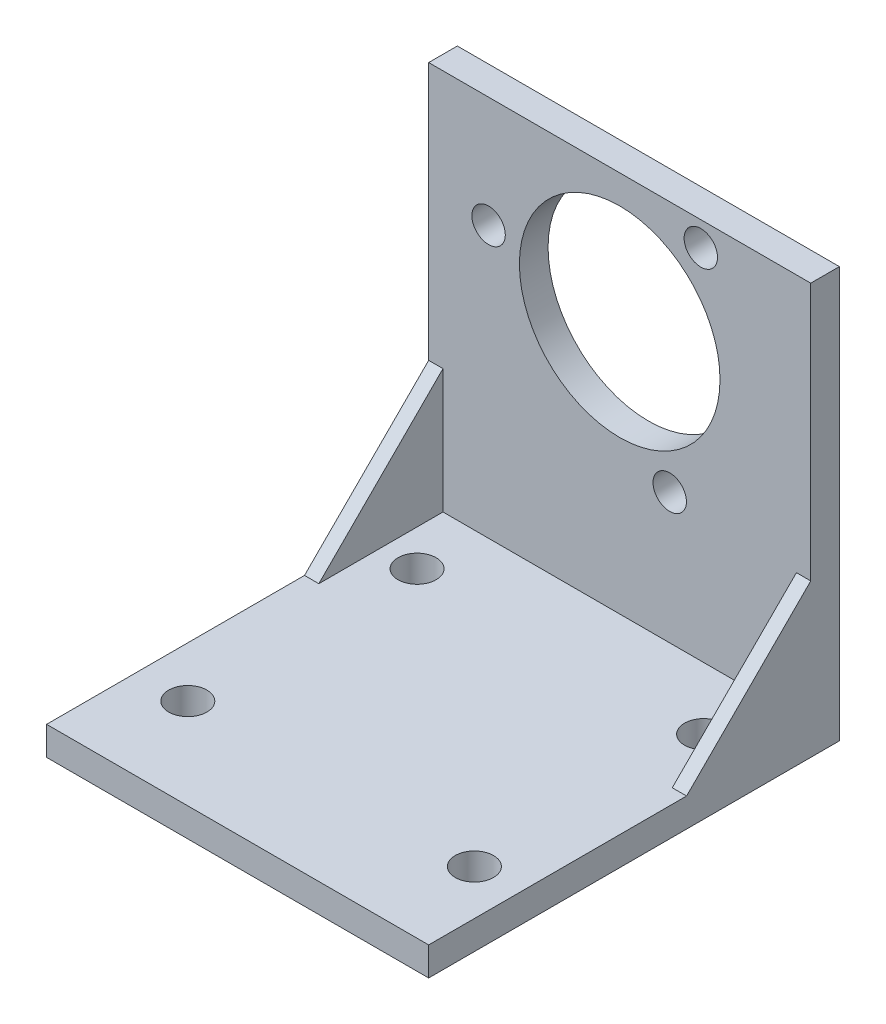
SolidWorks part; units mm, degrees
ref_plane "Front Plane" through (0, 0, 0) normal (0, 0, 1) x (1, 0, 0)
ref_plane "Top Plane" through (0, 0, 0) normal (0, 1, 0) x (1, 0, 0)
ref_plane "Right Plane" through (0, 0, 0) normal (1, 0, 0) x (0, 0, -1)
sketch "Sketch1" plane through (0, 0, 0) normal (0, 1, 0) x (1, 0, 0)
  line L0 (-20, 19.5) -> (20, 19.5)
  line L1 (-20, -21.5) -> (20, -21.5)
  line L2 (-20, -21.5) -> (-20, 21.5)
  line L3 (-20, 21.5) -> (20, 21.5)
  line L4 (20, -21.5) -> (20, 21.5)
  line L5 (-20, -21.5) -> (20, 21.5) construction
  line L6 (-20, 21.5) -> (20, -21.5) construction
  circle A7 centre (-14.7151, 12) radius 2
  circle A8 centre (15.2849, 12) radius 2
  circle A9 centre (-14.7151, -12) radius 2
  circle A10 centre (15.2849, -12) radius 2
  point P0 (0, 0)
  dimension "D4" = 30
  dimension "D5" = 4
  dimension "D6" = 4
  dimension "D7" = 24
  dimension "D8" = 9.5
  dimension "D9" = 5.2849
  dimension "D10" = 4
  dimension "D12" = 4
  dimension "D1" = 2
  dimension "D2" = 40
  dimension "D3" = 43
  dimension "D11" = 9.5
extrude "Boss-Extrude1" add sketch "Sketch1" against normal blind 3
sketch "Sketch4" plane through (0, 0, 0) normal (0, 1, 0) x (1, 0, 0)
  line L1 (-20, -21.5) -> (-20, 21.5) construction
  line L2 (20, -21.5) -> (20, 21.5) construction
  line L5 (-20, 21.5) -> (20, 21.5)
  line L6 (-20, 21.5) -> (-20, 18.5)
  line L7 (-20, 18.5) -> (20, 18.5)
  line L8 (-20, -21.5) -> (20, -21.5)
  line L9 (20, -21.5) -> (20, 21.5)
  line L10 (20, 21.5) -> (-20, 21.5)
  line L11 (-20, 21.5) -> (-20, -21.5)
  line L12 (-20, -21.5) -> (20, -21.5)
  line L13 (20, -21.5) -> (20, 12.2)
  line L15 (-20, 12.2) -> (-20, -21.5)
  line L16 (20, 21.5) -> (20, 18.5)
  line M13 (20, -21.5) -> (20, 21.5)
  line M14 (20, 21.5) -> (-20, 21.5)
  line M15 (-20, 21.5) -> (-20, -21.5)
  dimension "D1" = 3
  dimension "D2" = 0
extrude "Boss-Extrude2" add sketch "Sketch4" along normal blind 40 contours L7 M15 M13 M14
sketch "Sketch5" plane through (0, 0, -18.5) normal (0, 0, 1) x (1, 0, 0)
  line L0 (-20, 40) -> (20, -3) construction
  line L1 (-20, -3) -> (20, 40) construction
  line L2 (0, 26.5) -> (0, 40) construction
  line L5 (-20, 40) -> (20, 40) construction
  circle A0 centre (0, 26.5) radius 13.8564
  circle A2 centre (8.492, 37.4493) radius 1.75
  circle A3 centre (-13.7283, 28.3796) radius 1.75
  circle A4 centre (5.2364, 13.6711) radius 1.75
  circle A5 centre (0, 26.5) radius 10.5
  point P13 (0, 26.5)
  point P18 (0, 19.5)
  dimension "D2" = 24
  dimension "D3" = 24
  dimension "D4" = 13.5
  dimension "D5" = 3.5
  dimension "D1" = 24
  dimension "D6" = 3.5
  dimension "D7" = 3.5
extrude "Cut-Extrude1" cut sketch "Sketch5" against normal blind 24 contours A5 | A0 A3 | A0 A3 | A0 A4 | A0 A2 | A0 A2
sketch "Sketch7" plane through (20, 0, 0) normal (1, 0, 0) x (0, 0, -1)
  line L0 (18.5, 0) -> (18.5, 13)
  line L1 (18.5, 0) -> (5.5, 0)
  line L2 (21.5, 0) -> (-21.5, 0) construction
  line L3 (18.5, 13) -> (5.5, 0)
  dimension "D1" = 13
  dimension "D2" = 13
extrude "Boss-Extrude3" add sketch "Sketch7" against normal blind 1.5
sketch "Sketch8" plane through (-20, 0, 0) normal (-1, 0, 0) x (0, 0, 1)
  line L0 (-18.5, 0) -> (-18.5, 13)
  line L1 (-18.5, 0) -> (-5.5, 0)
  line L2 (-18.5, 13) -> (-5.5, 0)
extrude "Boss-Extrude4" add sketch "Sketch8" against normal blind 1.5
